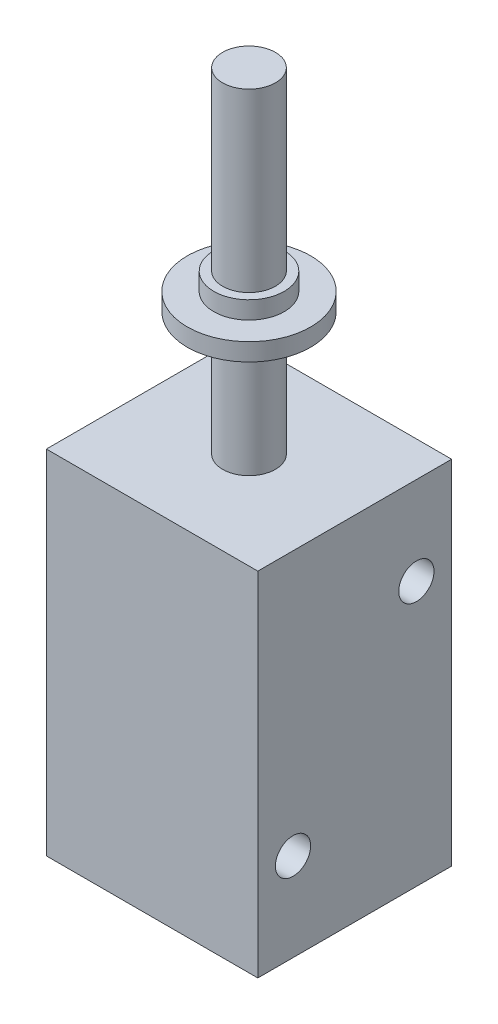
SolidWorks part; units mm, degrees
ref_plane "Front Plane" through (0, 0, 0) normal (0, 0, 1) x (1, 0, 0)
ref_plane "Top Plane" through (0, 0, 0) normal (0, 1, 0) x (1, 0, 0)
ref_plane "Right Plane" through (0, 0, 0) normal (1, 0, 0) x (0, 0, -1)
sketch "Sketch1" plane through (0, 0, 0) normal (0, 1, 0) x (1, 0, 0)
  line L1 (0, 0) -> (12, 0)
  line L2 (0, 0) -> (0, 11)
  line L3 (0, 11) -> (12, 11)
  line L4 (12, 0) -> (12, 11)
  dimension "D1" = 12
  dimension "D2" = 11
extrude "Boss-Extrude1" add sketch "Sketch1" along normal blind 20
sketch "Sketch2" plane through (0, 20, 0) normal (0, 1, 0) x (1, 0, 0)
  line L0 (-0.6033, 5.5) -> (12.6033, 5.5) construction
  line L1 (6, -0.6264) -> (6, 11.6264) construction
  line L2 (12, 11) -> (0, 11) construction
  line L3 (0, 11) -> (0, 0) construction
  circle A0 centre (6, 5.5) radius 1.5
  point P6 (6, 11)
  point P9 (0, 5.5)
  dimension "D1" = 3
extrude "Boss-Extrude2" add sketch "Sketch2" along normal blind 19
ref_plane "Plane1" through (0, 27, 0) normal (0, 1, 0) x (1, 0, 0)
sketch "Sketch3" plane through (0, 27, 0) normal (0, 1, 0) x (1, 0, 0)
  circle A0 centre (6, 5.5) radius 3.5
  dimension "D1" = 7
extrude "Boss-Extrude3" add sketch "Sketch3" along normal blind 1
sketch "Sketch4" plane through (0, 28, 0) normal (0, 1, 0) x (1, 0, 0)
  circle A0 centre (6, 5.5) radius 2
  dimension "D1" = 4
extrude "Boss-Extrude4" add sketch "Sketch4" along normal blind 1
sketch "Sketch5" plane through (12, 0, 0) normal (1, 0, 0) x (0, 0, -1)
  line L0 (11, 20) -> (11, 0) construction
  line L1 (0, 20) -> (0, 0) construction
  line L2 (0, 0) -> (11, 0) construction
  line L3 (0, 20) -> (11, 20) construction
  circle A0 centre (2, 5) radius 1
  circle A1 centre (9, 15) radius 1
  dimension "D3" = 2
  dimension "D4" = 2
  dimension "D1" = 2
  dimension "D2" = 2
  dimension "D5" = 5
  dimension "D6" = 5
extrude "Cut-Extrude1" cut sketch "Sketch5" against normal up to surface (12 mm away) up to face at (0, 10, -5.5)
